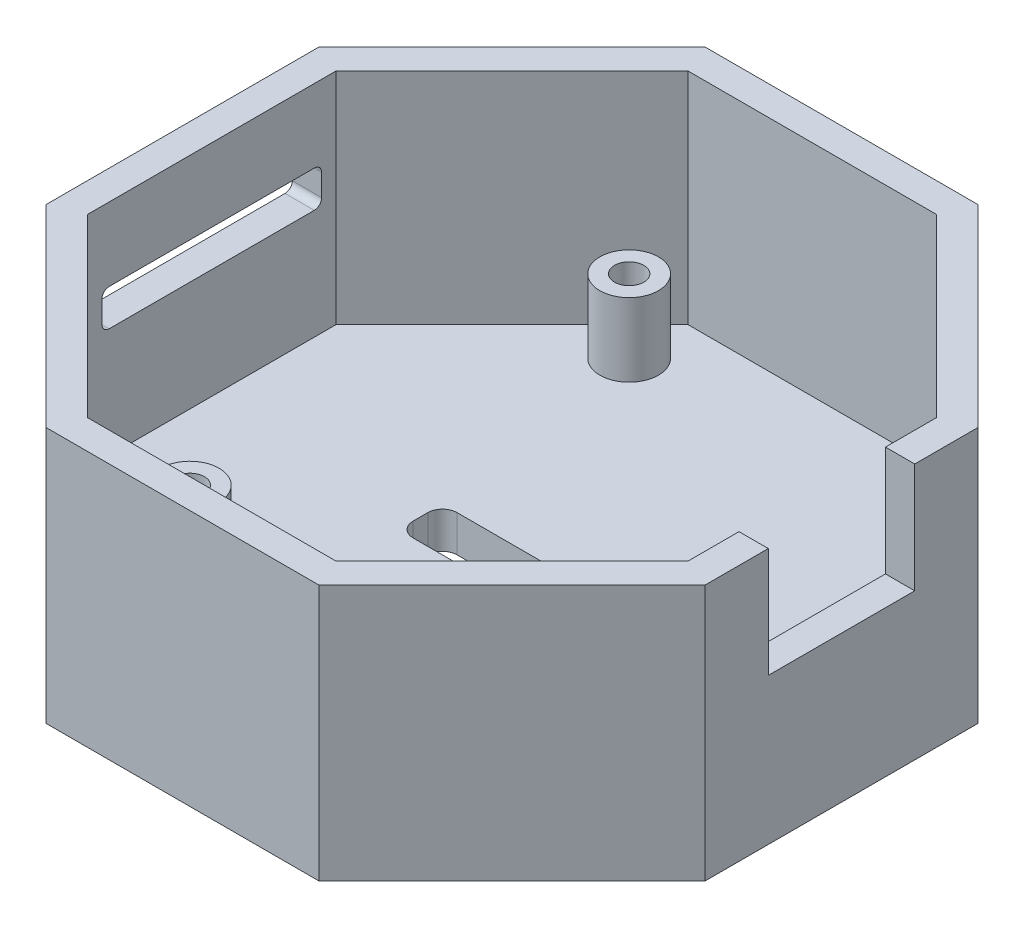
SolidWorks part; units mm, degrees
ref_plane "前视基准面" through (0, 0, 0) normal (0, 0, 1) x (1, 0, 0)
ref_plane "上视基准面" through (0, 0, 0) normal (0, 1, 0) x (1, 0, 0)
ref_plane "右视基准面" through (0, 0, 0) normal (1, 0, 0) x (0, 0, -1)
other "Configuration Table"
sketch "草图1" plane through (0, 0, 0) normal (0, 1, 0) x (1, 0, 0)
  line L10 (45, 18.6396) -> (18.6396, 45)
  line L11 (18.6396, 45) -> (-18.6396, 45)
  line L12 (-18.6396, 45) -> (-45, 18.6396)
  line L13 (-45, 18.6396) -> (-45, -18.6396)
  line L14 (-45, -18.6396) -> (-18.6396, -45)
  line L15 (-18.6396, -45) -> (18.6396, -45)
  line L16 (18.6396, -45) -> (45, -18.6396)
  line L17 (45, -18.6396) -> (45, 18.6396)
  circle A0 centre (0, 0) radius 45 construction
extrude "凸台-拉伸1" add sketch "草图1" along normal blind 5 contours L10 L11 L12 L13 L14 L15 L16 L17
sketch "草图5" plane through (0, 5, 0) normal (0, 1, 0) x (1, 0, 0)
  line L1 (41, 16.9828) -> (16.9828, 41)
  line L2 (16.9828, 41) -> (-16.9828, 41)
  line L3 (-16.9828, 41) -> (-41, 16.9828)
  line L4 (-41, 16.9828) -> (-41, -16.9828)
  line L5 (-41, -16.9828) -> (-16.9828, -41)
  line L6 (-16.9828, -41) -> (16.9828, -41)
  line L7 (16.9828, -41) -> (41, -16.9828)
  line L8 (41, -16.9828) -> (41, 16.9828)
  line L16 (45, -18.6396) -> (45, 18.6396)
  line L17 (45, 18.6396) -> (18.6396, 45)
  line L18 (18.6396, 45) -> (-18.6396, 45)
  line L19 (-18.6396, 45) -> (-45, 18.6396)
  line L20 (-45, 18.6396) -> (-45, -18.6396)
  line L21 (-45, -18.6396) -> (-18.6396, -45)
  line L22 (-18.6396, -45) -> (18.6396, -45)
  line L23 (18.6396, -45) -> (45, -18.6396)
  line L24 (45, -18.6396) -> (45, 18.6396)
  line L25 (45, 18.6396) -> (18.6396, 45)
  line L26 (18.6396, 45) -> (-18.6396, 45)
  line L27 (-18.6396, 45) -> (-45, 18.6396)
  line L28 (-45, 18.6396) -> (-45, -18.6396)
  line L29 (-45, -18.6396) -> (-18.6396, -45)
  line L30 (-18.6396, -45) -> (18.6396, -45)
  line L31 (18.6396, -45) -> (45, -18.6396)
  circle A0 centre (0, 0) radius 41 construction
  dimension "D1" = 0
extrude "凸台-拉伸3" add sketch "草图5" along normal blind 30
sketch "草图6" plane through (0, 5, 0) normal (0, 1, 0) x (1, 0, 0)
  circle A0 centre (-17, 33) radius 4
  circle A1 centre (-17, 33) radius 2
  circle A2 centre (10, -33) radius 4
  circle A3 centre (10, -33) radius 2
  circle A4 centre (-22, -22) radius 4
  circle A5 centre (-22, -22) radius 2
extrude "凸台-拉伸4" add sketch "草图6" along normal blind 10
sketch "草图7" plane through (0, 5, 0) normal (0, 1, 0) x (1, 0, 0)
  line L1 (-10.5, -3) -> (10.5, -3)
  line L2 (-12.5, -1) -> (-12.5, 1)
  line L3 (-10.5, 3) -> (10.5, 3)
  line L4 (12.5, -1) -> (12.5, 1)
  line L5 (-12.5, -3) -> (12.5, 3) construction
  line L6 (-12.5, 3) -> (12.5, -3) construction
  arc A0 (-10.5, -3) -> (-12.5, -1) centre (-10.5, -1) cw
  arc A1 (10.5, -3) -> (12.5, -1) centre (10.5, -1) ccw
  arc A2 (-12.5, 1) -> (-10.5, 3) centre (-10.5, 1) cw
  arc A3 (10.5, 3) -> (12.5, 1) centre (10.5, 1) cw
  point P0 (0, 0)
  dimension "D3" = 2
  dimension "D1" = 25
  dimension "D2" = 6
extrude "切除-拉伸1" cut sketch "草图7" against normal blind 10 contours A3 L3 A2 L2 A0 L1 A1 L4
ref_plane "基准面5" through (0, 15, 0) normal (0, 1, 0) x (1, 0, 0)
sketch "草图10" plane through (-45, 0, 0) normal (-1, 0, 0) x (0, 0, 1)
  line L2 (0, 20) -> (14, 20)
  line L3 (15, 21) -> (15, 24)
  line L4 (14, 25) -> (-14, 25)
  line L5 (-15, 24) -> (-15, 21)
  line L6 (-14, 20) -> (0, 20)
  arc A0 (-14, 25) -> (-15, 24) centre (-14, 24) ccw
  arc A1 (-15, 21) -> (-14, 20) centre (-14, 21) ccw
  arc A2 (15, 24) -> (14, 25) centre (14, 24) ccw
  arc A3 (14, 20) -> (15, 21) centre (14, 21) ccw
  dimension "D1" = 1
extrude "切除-拉伸3" cut sketch "草图10" against normal blind 10
sketch "草图11" plane through (0, 35, 0) normal (0, 1, 0) x (1, 0, 0)
  line L0 (41, 0) -> (41, 10)
  line L1 (41, -16.9828) -> (41, 16.9828) construction
  line L2 (41, 10) -> (45, 10)
  line L3 (45, -18.6396) -> (45, 18.6396) construction
  line L4 (45, 10) -> (45, -10)
  line L5 (45, -10) -> (41, -10)
  line L6 (41, -10) -> (41, 0)
extrude "切除-拉伸4" cut sketch "草图11" against normal blind 15
